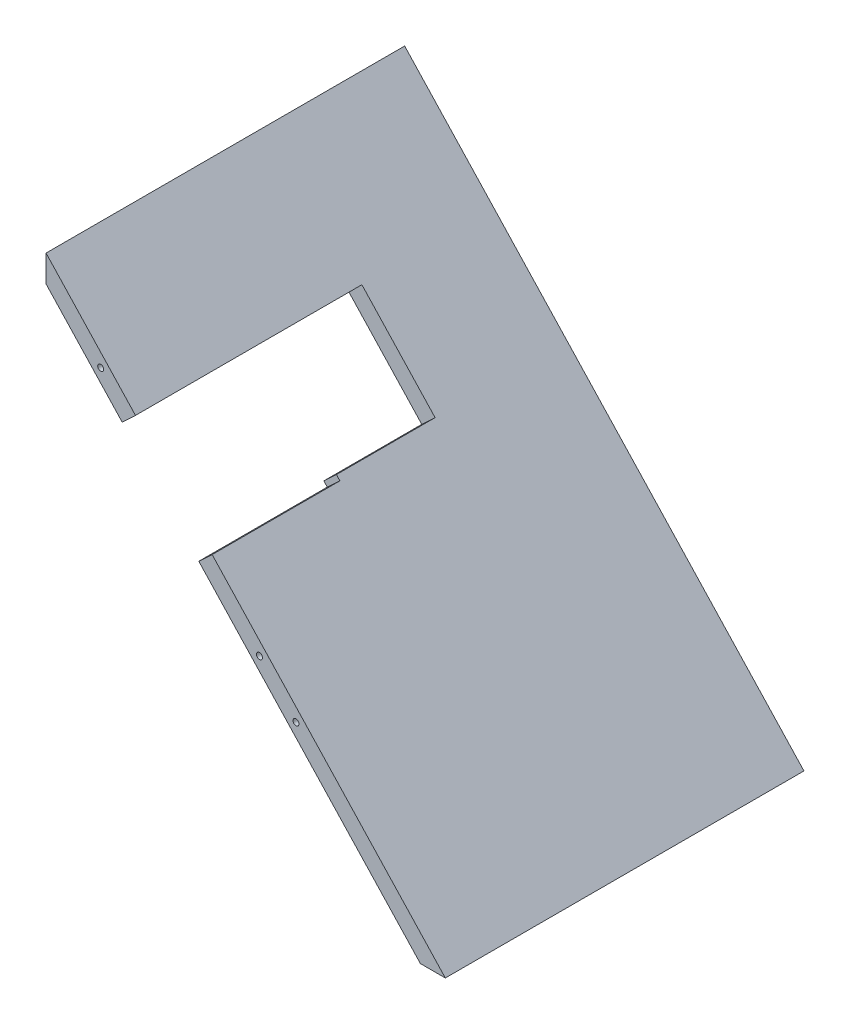
SolidWorks part; units mm, degrees
ref_plane "Front Plane" through (0, 0, 0) normal (0, 0, 1) x (1, 0, 0)
ref_plane "Top Plane" through (0, 0, 0) normal (0, 1, 0) x (1, 0, 0)
ref_plane "Right Plane" through (0, 0, 0) normal (1, 0, 0) x (0, 0, -1)
sketch "Sketch1" plane through (0, 0, 0) normal (0, 0, 1) x (1, 0, 0)
  line L0 (0, 0) -> (177.6441, 0)
  line L1 (177.6441, 0) -> (0, 190.5)
  line L2 (0, 190.5) -> (0, 0)
  line L3 (0, 190.5) -> (0, 203.2)
  line L4 (0, 203.2) -> (189.4871, 0)
  line L5 (189.4871, 0) -> (177.6441, 0)
  dimension "D1" = 47
  dimension "D2" = 12.7
  dimension "D3" = 203.2
extrude "Boss-Extrude1" add sketch "Sketch1" along normal blind 170.18 contours L5 L4 L3 L1
sketch "Sketch2" plane through (101.3525, 94.5127, 0) normal (0.7314, 0.682, 0) x (0, 0, -1)
  line L0 (-170.18, 148.6111) -> (-170.18, -129.2299) construction
  line L1 (-170.18, 86.3811) -> (-62.738, 86.3811)
  line L2 (-170.18, 86.3811) -> (-170.18, 33.0411)
  line L3 (-170.18, 33.0411) -> (-62.738, 33.0411)
  line L4 (-62.738, 86.3811) -> (-62.738, 33.0411)
  dimension "D1" = 62.23
  dimension "D2" = 53.34
  dimension "D3" = 107.442
extrude "Cut-Extrude1" cut sketch "Sketch2" against normal blind 170.18
sketch "Sketch3" plane through (101.3525, 94.5127, 0) normal (0.7314, 0.682, 0) x (0, 0, -1)
  line L1 (-62.738, 33.0411) -> (-109.5596, 33.0411)
  line L2 (-62.738, 33.0411) -> (-62.738, 35.443)
  line L3 (-62.738, 35.443) -> (-109.5596, 35.443)
  line L4 (-109.5596, 33.0411) -> (-109.5596, 35.443)
extrude "Boss-Extrude2" add sketch "Sketch3" against normal blind 8.1534
sketch "Sketch4" plane through (0, 0, 170.18) normal (0, 0, 1) x (1, 0, 0)
  line L0 (0, 196.85) -> (183.5656, 0) construction
  line L1 (0, 190.5) -> (0, 203.2) construction
  line L2 (189.4871, 0) -> (177.6441, 0) construction
  circle A0 centre (25.9285, 169.0451) radius 1.4224
  circle A1 centre (101.2825, 88.2378) radius 1.4224
  circle A2 centre (118.6053, 69.6614) radius 1.4224
  dimension "D1" = 25.4
  dimension "D2" = 95.25
  dimension "D3" = 110.49
extrude "Cut-Extrude2" cut sketch "Sketch4" against normal blind 10.16
ref_plane "Plane1" through (0, 0, 85.09) normal (0, 0, 1) x (1, 0, 0)
mirror "Mirror1" about plane through (0, 0, 85.09) normal (0, 0, 1) of "Cut-Extrude2"
